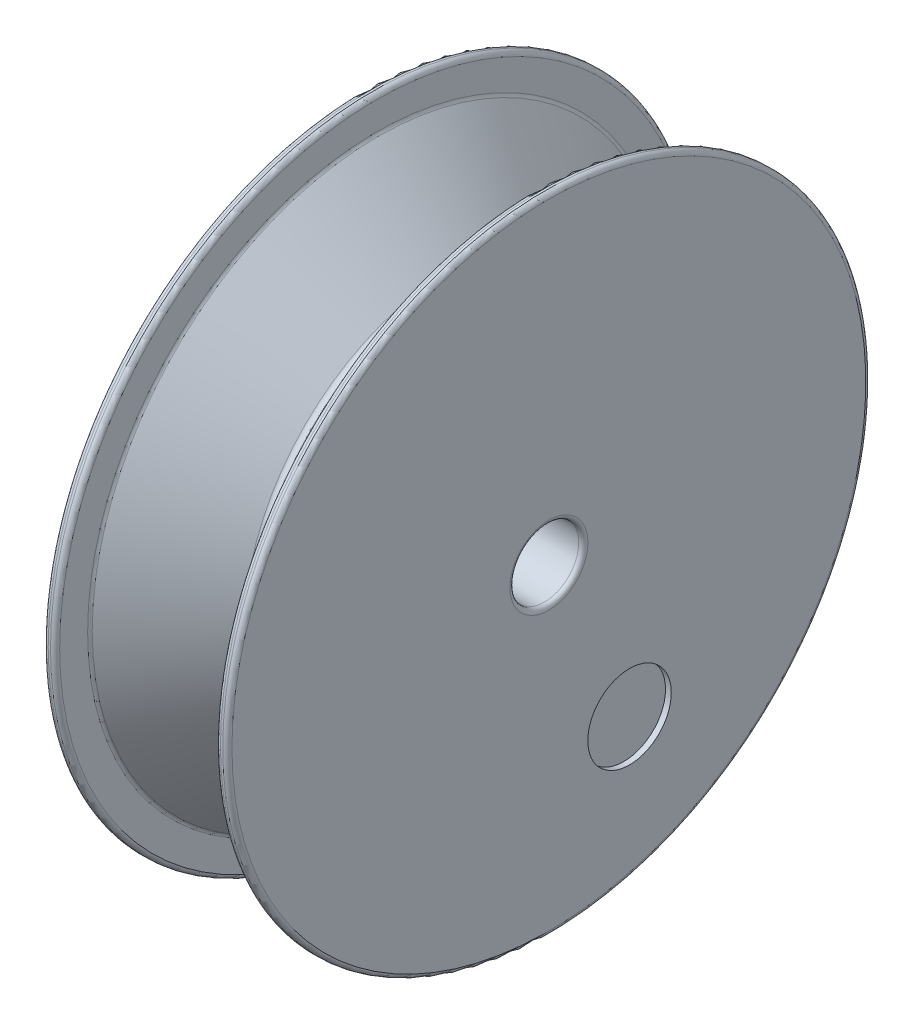
SolidWorks part; units mm, degrees
ref_plane "Face" through (0, 0, 0) normal (0, 0, 1) x (1, 0, 0)
ref_plane "Dessus" through (0, 0, 0) normal (0, 1, 0) x (1, 0, 0)
ref_plane "Droite" through (0, 0, 0) normal (1, 0, 0) x (0, 0, -1)
sketch "Esquisse1" plane through (0, 0, 0) normal (0, 0, 1) x (1, 0, 0)
  line L1 (-3.5, 12.5) -> (0, 9)
  line L3 (4, 1.5) -> (4, 14)
  line L4 (-4, 14) -> (-3.5, 14)
  line L5 (-4, 1.5) -> (-4, 14)
  line L6 (0, 9) -> (3.5, 12.5)
  line L7 (-3.5, 14) -> (-3.5, 12.5)
  line L8 (3.5, 12.5) -> (3.5, 14)
  line L9 (4, 14) -> (3.5, 14)
  line L10 (-4, 1.5) -> (4, 1.5)
  line L12 (0, 0) -> (68.6205, 0) construction
  dimension "D8" = 3.5
  dimension "D1" = 4
  dimension "D2" = 8
  dimension "D3" = 1.5
  dimension "D4" = 0.5
  dimension "D5" = 0.5
  dimension "D6" = 1.5
  dimension "D7" = 3.5
  dimension "D9" = 3.5
  dimension "D10" = 12.5
revolve "Révolution2" add sketch "Esquisse1" angle 360 about L12
fillet "Congé1" radius 0.2
sketch "Esquisse2" plane through (4, 0, 0) normal (1, 0, 0) x (0, 0, -1)
  circle A0 centre (3.5119, -7.4726) radius 1.8173
extrude "Enlèv. mat.-Extru.1" cut sketch "Esquisse2" against normal blind 0.25
